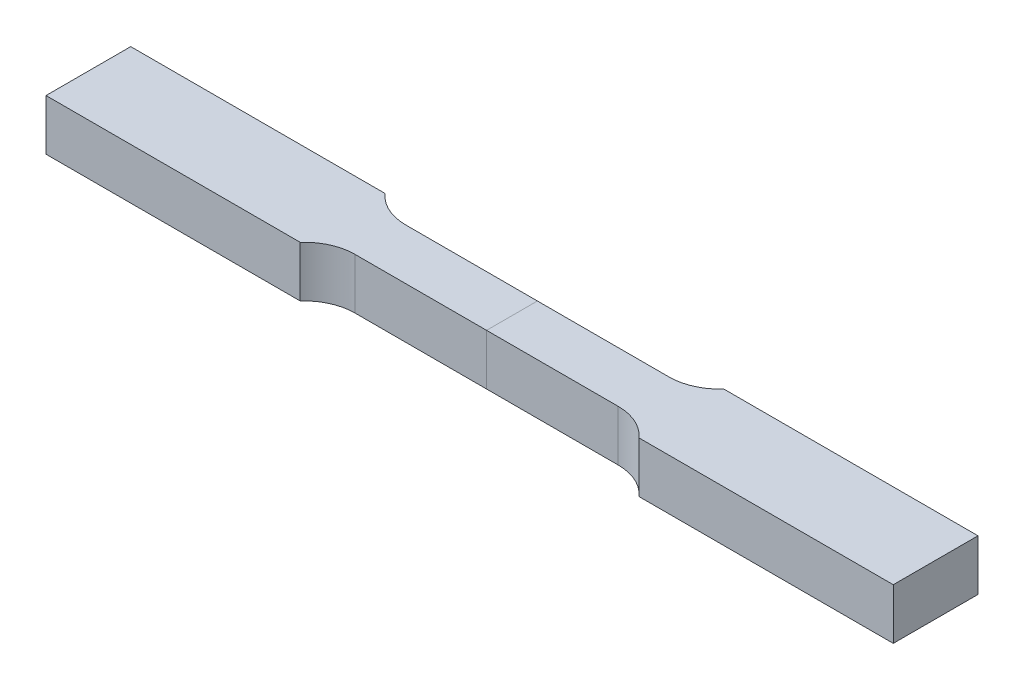
SolidWorks part; units mm, degrees
ref_plane "Front" through (0, 0, 0) normal (0, 0, 1) x (1, 0, 0)
ref_plane "Top" through (0, 0, 0) normal (0, 1, 0) x (1, 0, 0)
ref_plane "Right" through (0, 0, 0) normal (1, 0, 0) x (0, 0, -1)
sketch "Sketch1" plane through (0, 0, 0) normal (0, 1, 0) x (1, 0, 0)
  line L0 (0, 32.0696) -> (0, -21.7429) construction
  line L1 (0, -3) -> (0, 3)
  line L2 (0, 3) -> (-15.5279, 3)
  line L4 (-20, 5) -> (-50, 5)
  line L5 (-50, 5) -> (-50, -5)
  line L6 (-50, -5) -> (-20, -5)
  line L8 (-15.5279, -3) -> (0, -3)
  arc A0 (-20, -5) -> (-15.5279, -3) centre (-15.5279, -9) cw
  arc A1 (-15.5279, 3) -> (-20, 5) centre (-15.5279, 9) cw
  point P3 (0, 0)
  dimension "D4" = 6
  dimension "D1" = 10
  dimension "D2" = 50
  dimension "D3" = 6
  dimension "D5" = 30
extrude "Boss-Extrude1" add sketch "Sketch1" along normal blind 6
mirror "Mirror1" about plane through (0, 0, 0) normal (1, 0, 0) of bodies 101
